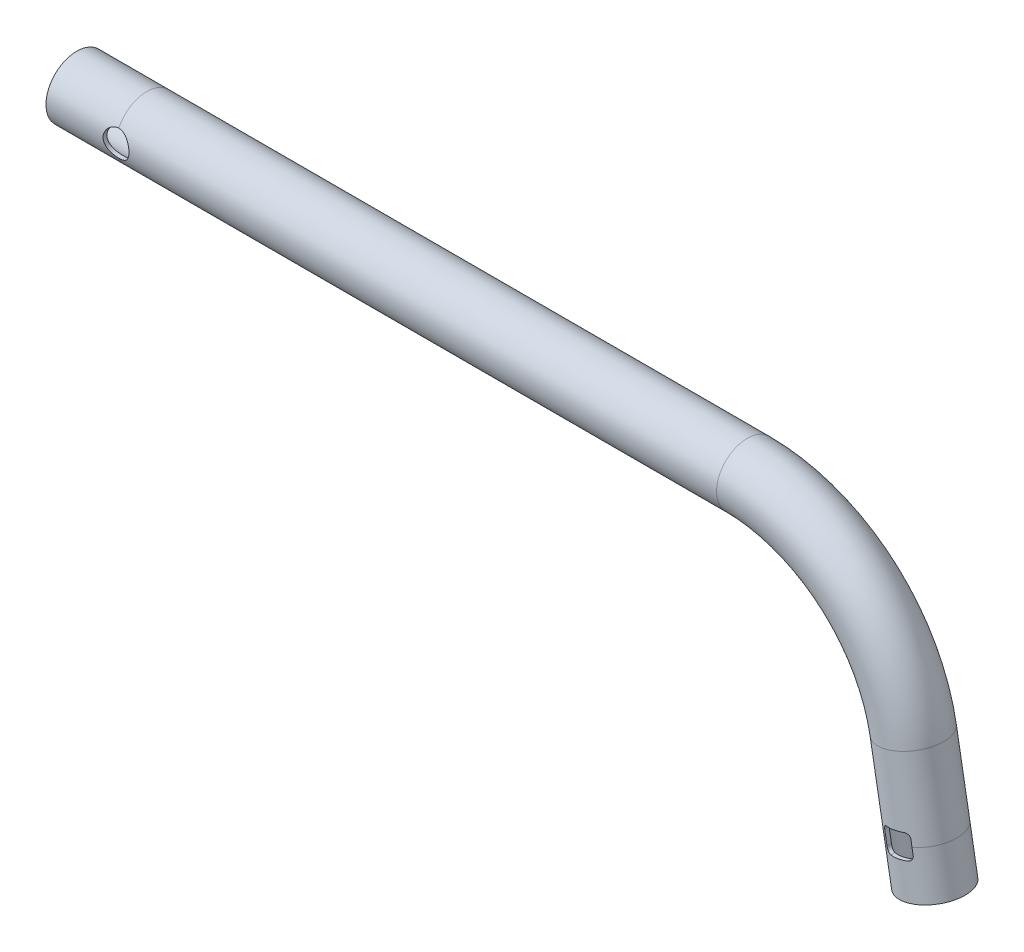
SolidWorks part; units mm, degrees
ref_plane "Front Plane" through (0, 0, 0) normal (0, 0, 1) x (1, 0, 0)
ref_plane "Top Plane" through (0, 0, 0) normal (0, 1, 0) x (1, 0, 0)
ref_plane "Right Plane" through (0, 0, 0) normal (1, 0, 0) x (0, 0, -1)
sketch "Sketch1" plane through (0, 0, 0) normal (0, 0, 1) x (1, 0, 0)
  line L0 (0, 0) -> (185.3734, 0)
  line L1 (236.5834, -42.9703) -> (240.75, -66.6)
  line L2 (0, 0) -> (-21.6, 0)
  line L3 (240.75, -66.6) -> (243.2362, -80.7)
  arc A0 (236.5834, -42.9703) -> (185.3734, 0) centre (185.3734, -52) ccw
  point P6 (0, 0)
  point P10 (240.75, -66.6)
  dimension "D2" = 52
  dimension "D1" = 80
  dimension "D3" = 240.75
  dimension "D4" = 66.6
  dimension "D5" = 21.6
  dimension "D6" = 80.7
ref_plane "Plane1" through (-21.6, 0, 0) normal (-1, 0, 0) x (0, 0, 1)
sketch "Sketch2" plane through (-21.6, 0, 0) normal (-1, 0, 0) x (0, 0, 1)
  circle A0 centre (0, 0) radius 9.5
  circle A1 centre (0, 0) radius 8.3
  dimension "D1" = 1.2
sweep "Sweep1" add profiles "Sketch2" path "Sketch1"
sketch "Sketch3" plane through (0, 0, 0) normal (0, 0, 1) x (1, 0, 0)
  line L0 (240.75, -66.6) -> (244.7877, -65.888) construction
  line L1 (231.3943, -68.2497) -> (250.1057, -64.9503) construction
  line L2 (240.75, -66.6) -> (240.1335, -63.1039) construction
  line L3 (245.1495, -67.9399) -> (244.4259, -63.8361)
  line L4 (242.6882, -62.6194) -> (237.5672, -63.5224)
  line L5 (236.3505, -65.2601) -> (237.0741, -69.3639)
  line L6 (238.8118, -70.5806) -> (243.9328, -69.6776)
  arc A0 (238.8118, -70.5806) -> (237.0741, -69.3639) centre (238.5513, -69.1034) cw
  arc A1 (243.9328, -69.6776) -> (245.1495, -67.9399) centre (243.6723, -68.2004) ccw
  arc A2 (244.4259, -63.8361) -> (242.6882, -62.6194) centre (242.9487, -64.0966) ccw
  arc A3 (237.5672, -63.5224) -> (236.3505, -65.2601) centre (237.8277, -64.9996) ccw
  point P8 (244.7877, -65.888)
  point P14 (245.41, -69.4172)
  point P17 (244.1654, -62.3589)
  point P20 (236.09, -63.7828)
  dimension "D6" = 1.5
  dimension "D1" = 4.1
  dimension "D2" = 3.55
  dimension "D3" = 90
  dimension "D4" = 7.1671
  dimension "D5" = 8.2
extrude "Cut-Extrude1" cut sketch "Sketch3" against normal up to next and the other way up to next
sketch "Sketch4" plane through (0, 0, 0) normal (0, 0, 1) x (1, 0, 0)
  line L0 (0, -9.5) -> (0, 9.5) construction
  circle A0 centre (0, 0) radius 4
extrude "Cut-Extrude2" cut sketch "Sketch4" along normal up to next
